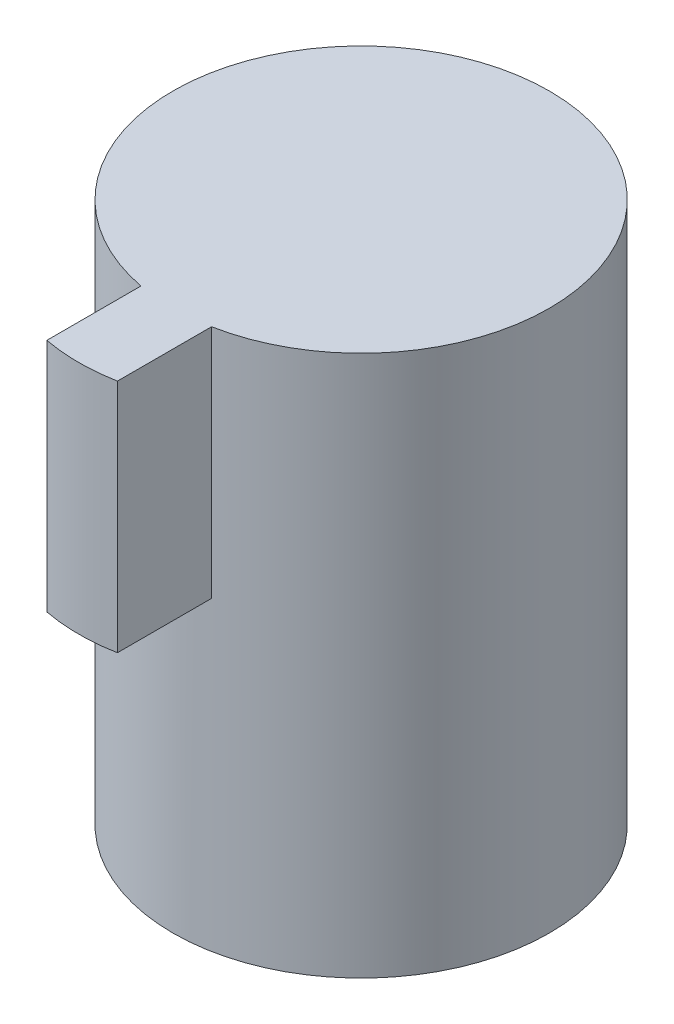
SolidWorks part; units mm, degrees
ref_plane "Plan de face" through (0, 0, 0) normal (0, 0, 1) x (1, 0, 0)
ref_plane "Plan de dessus" through (0, 0, 0) normal (0, 1, 0) x (1, 0, 0)
ref_plane "Plan de droite" through (0, 0, 0) normal (1, 0, 0) x (0, 0, -1)
sketch "Esquisse1" plane through (0, 0, 0) normal (0, 0, 1) x (1, 0, 0)
  line L0 (0, 0) -> (0, 10) construction
  line L1 (2.5, 0) -> (2.5, 10)
  line L2 (2.5, 10) -> (0, 10)
  line L3 (0, 10) -> (0, 11.5)
  line L4 (0, 11.5) -> (4, 11.5)
  line L5 (4, 11.5) -> (4, 0)
  line L6 (4, 0) -> (2.5, 0)
  dimension "D1" = 5
  dimension "D2" = 1.5
  dimension "D3" = 10
revolve "Révolution1" add sketch "Esquisse1" angle 360 about L0
sketch "Esquisse2" plane through (0, 0, 0) normal (0, 0, 1) x (1, 0, 0)
  line L0 (4, 11.5) -> (-4, 11.5) construction
  line L1 (0.75, 6.5) -> (-0.75, 6.5)
  line L2 (0.75, 6.5) -> (0.75, 11.5)
  line L3 (0.75, 11.5) -> (-0.75, 11.5)
  line L4 (-0.75, 6.5) -> (-0.75, 11.5)
  line L5 (0.75, 6.5) -> (-0.75, 11.5) construction
  line L6 (0.75, 11.5) -> (-0.75, 6.5) construction
  point P0 (0, 9)
  point P5 (0, 0)
  dimension "D1" = 1.5
  dimension "D2" = 5
extrude "Boss.-Extru.1" add sketch "Esquisse2" along normal blind 2 from surface starting at face at (4, 11.5, 0)
